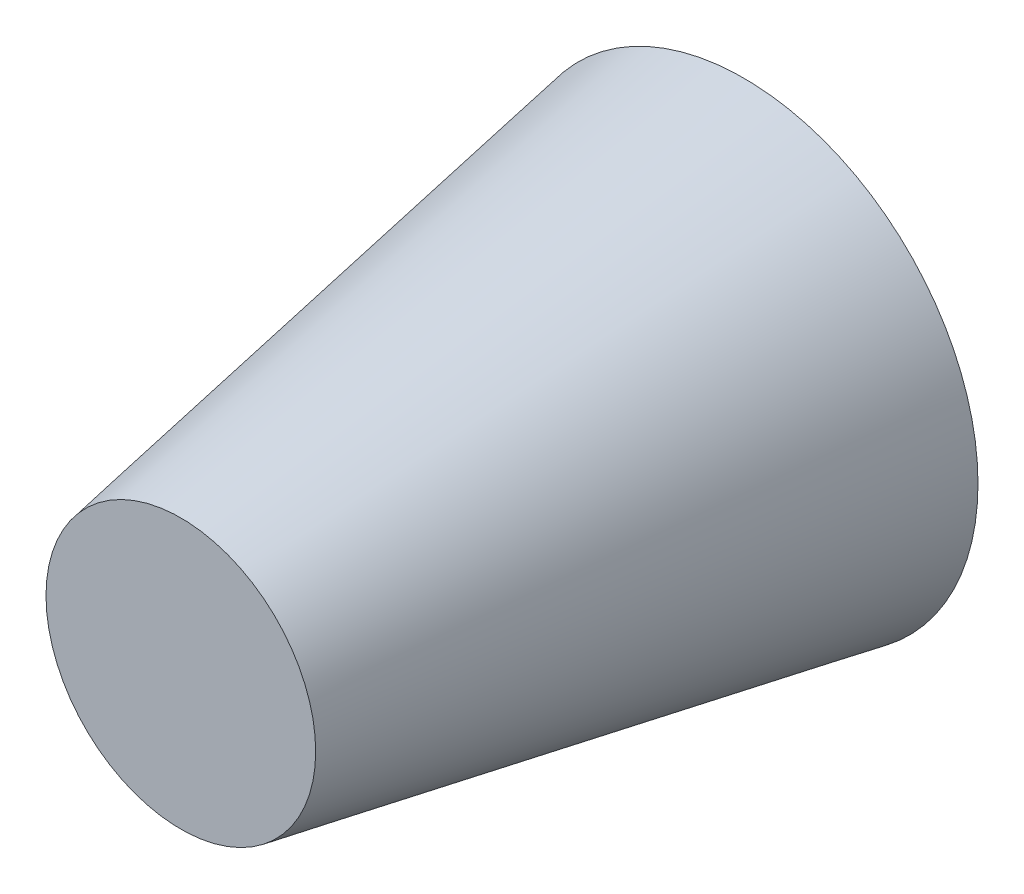
SolidWorks part; units mm, degrees
ref_plane "Front Plane" through (0, 0, 0) normal (0, 0, 1) x (1, 0, 0)
ref_plane "Top Plane" through (0, 0, 0) normal (0, 1, 0) x (1, 0, 0)
ref_plane "Right Plane" through (0, 0, 0) normal (1, 0, 0) x (0, 0, -1)
sketch "Sketch1" plane through (0, 0, 0) normal (0, 0, 1) x (1, 0, 0)
  circle A0 centre (0, 40.7625) radius 20.7901
extrude "Boss-Extrude1" add sketch "Sketch1" along normal blind 50 draft 10 contours A0
